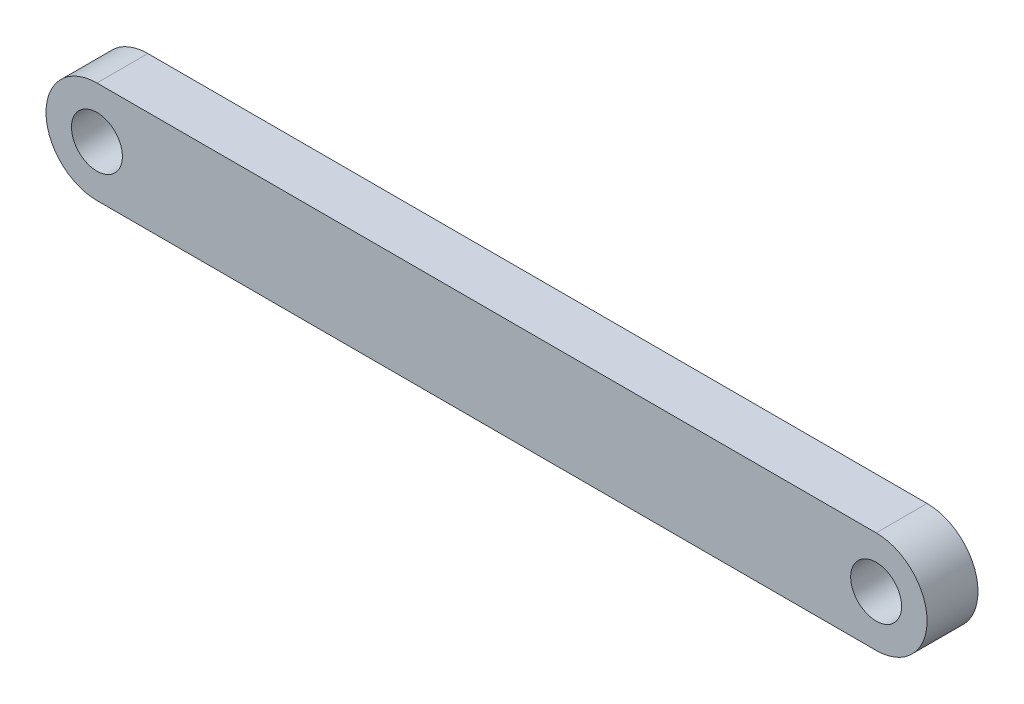
SolidWorks part; units mm, degrees
ref_plane "前视基准面" through (0, 0, 0) normal (0, 0, 1) x (1, 0, 0)
ref_plane "上视基准面" through (0, 0, 0) normal (0, 1, 0) x (1, 0, 0)
ref_plane "右视基准面" through (0, 0, 0) normal (1, 0, 0) x (0, 0, -1)
sketch "草图1" plane through (0, 0, 0) normal (0, 0, 1) x (1, 0, 0)
  line L0 (0, 0) -> (153, 0) construction
  line L1 (0, 10) -> (153, 10)
  line L2 (0, -10) -> (153, -10)
  arc A0 (0, 10) -> (0, -10) centre (0, 0) ccw
  arc A1 (153, -10) -> (153, 10) centre (153, 0) ccw
  circle A2 centre (0, 0) radius 5
  circle A3 centre (153, 0) radius 5
  point P3 (76.5, 0)
  dimension "D1" = 10
  dimension "D2" = 10
  dimension "D3" = 153
extrude "凸台-拉伸1" add sketch "草图1" along normal blind 10
